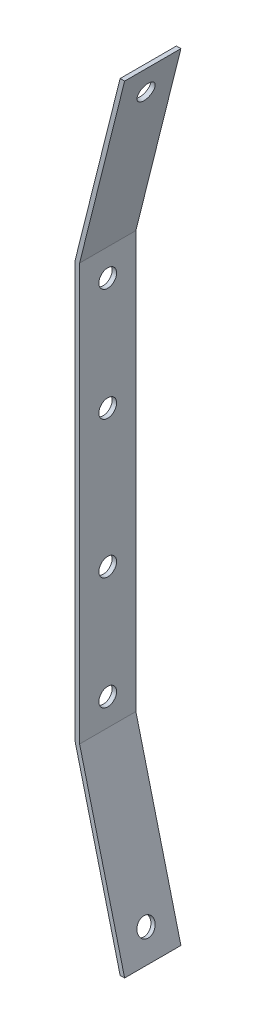
SolidWorks part; units mm, degrees
ref_plane "Front Plane" through (0, 0, 0) normal (0, 0, 1) x (1, 0, 0)
ref_plane "Top Plane" through (0, 0, 0) normal (0, 1, 0) x (1, 0, 0)
ref_plane "Right Plane" through (0, 0, 0) normal (1, 0, 0) x (0, 0, -1)
sketch "Sketch1" plane through (0, 0, 0) normal (0, 0, 1) x (1, 0, 0)
  line L0 (0.508, 46.99) -> (5.588, 67.31)
  line L1 (0, 0) -> (0.508, 0)
  line L2 (0, 0) -> (0, 46.99)
  line L3 (0, 46.99) -> (0.508, 46.99)
  line L4 (0.508, 0) -> (0.508, 46.99)
  line L5 (5.588, 67.31) -> (0, 67.31)
  line L6 (0, 67.31) -> (0, 46.99)
  line L7 (0, 46.99) -> (5.08, 67.31)
  line L8 (0, 0) -> (0, -20.32)
  line L9 (0, -20.32) -> (5.588, -20.32)
  line L10 (5.588, -20.32) -> (0.508, 0)
  line L11 (0, 0) -> (5.08, -20.32)
  dimension "D1" = 46.99
  dimension "D2" = 20.32
  dimension "D3" = 90
  dimension "D4" = 5.588
  dimension "D5" = 0.508
  dimension "D6" = 0.508
  dimension "D7" = 20.32
  dimension "D8" = 5.588
  dimension "D9" = 0.508
extrude "Boss-Extrude1" add sketch "Sketch1" along normal blind 6.35 contours L1 L4 L3 L2 | L7 L3 L0 L5 | L1 L11 L9 L10
sketch "Sketch2" plane through (0, 0, 0) normal (-1, 0, 0) x (0, 0, 1)
  line L1 (0, 0) -> (0, 46.99) construction
  line L2 (6.35, 0) -> (6.35, 46.99) construction
  line L3 (6.35, 0) -> (0, 0) construction
  line L4 (6.35, 46.99) -> (0, 46.99) construction
  line L5 (6.35, 0) -> (6.35, 46.99) construction
  circle A0 centre (3.175, 3.048) radius 1
  circle A1 centre (3.175, 15.748) radius 1
  circle A2 centre (3.175, 43.942) radius 1
  circle A3 centre (3.175, 31.242) radius 1
  point P16 (3.175, 46.99)
  dimension "D1" = 3.048
  dimension "D2" = 3.175
  dimension "D3" = 2
  dimension "D4" = 2
  dimension "D5" = 12.7
  dimension "D6" = 3.175
  dimension "D7" = 2
  dimension "D8" = 2
  dimension "D9" = 3.048
  dimension "D10" = 12.7
  dimension "D11" = 3.175
  dimension "D12" = 3.175
extrude "Cut-Extrude1" cut sketch "Sketch2" against normal blind 6.35
sketch "Sketch3" plane through (-11.0565, 2.7641, 0) normal (-0.9701, 0.2425, 0) x (0, 0, 1)
  line L0 (6.35, 45.587) -> (6.35, 66.5324) construction
  line L1 (6.35, 66.5324) -> (0, 66.5324) construction
  circle A0 centre (3.175, 63.5324) radius 1
  dimension "D1" = 2
  dimension "D2" = 3.175
  dimension "D3" = 3
extrude "Cut-Extrude2" cut sketch "Sketch3" against normal blind 6.35
sketch "Sketch4" plane through (0.4781, 0.1195, 0) normal (0.9701, 0.2425, 0) x (0, 0, -1)
  line L0 (0, -21.0686) -> (0, -0.1232) construction
  line L3 (-6.35, -20.9454) -> (0, -20.9454) construction
  circle A0 centre (-3.175, -17.9454) radius 1
  ellipse E0 centre (-3.175, 61.1892) end of major axis (-2.175, 61.1892) minor radius 0.8824 construction
  point P10 (-3.8821, 61.8131)
  dimension "D1" = 2
  dimension "D2" = 3.175
  dimension "D3" = 3
extrude "Cut-Extrude3" cut sketch "Sketch4" against normal blind 2.54
